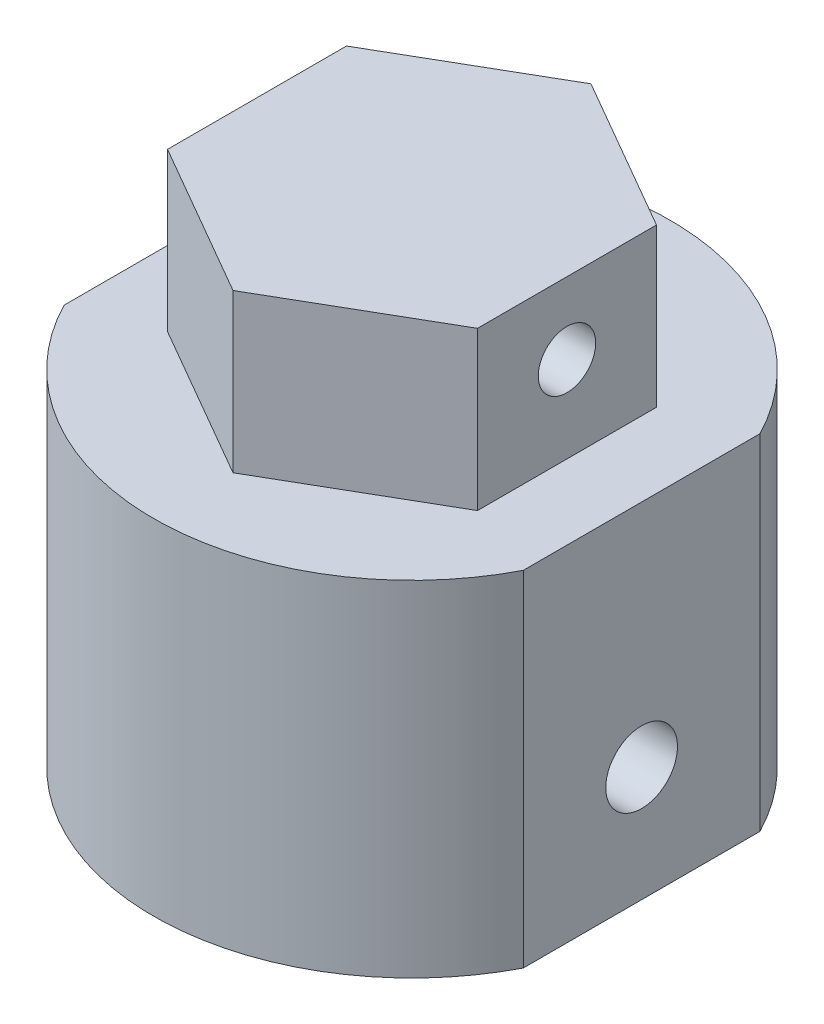
SolidWorks part; units mm, degrees
ref_plane "Plano frontal" through (0, 0, 0) normal (0, 0, 1) x (1, 0, 0)
ref_plane "Plano superior" through (0, 0, 0) normal (0, 1, 0) x (1, 0, 0)
ref_plane "Plano direito" through (0, 0, 0) normal (1, 0, 0) x (0, 0, -1)
sketch "Esboço1" plane through (0, 0, 0) normal (0, 1, 0) x (1, 0, 0)
  circle A0 centre (0, 0) radius 9
  dimension "D1" = 18
extrude "Ressalto-extrusão1" add sketch "Esboço1" along normal blind 12
sketch "Esboço2" plane through (0, 12, 0) normal (0, 1, 0) x (1, 0, 0)
  line L1 (0, 6.2354) -> (-5.4, 3.1177)
  line L2 (-5.4, 3.1177) -> (-5.4, -3.1177)
  line L3 (-5.4, -3.1177) -> (0, -6.2354)
  line L4 (0, -6.2354) -> (5.4, -3.1177)
  line L5 (5.4, -3.1177) -> (5.4, 3.1177)
  line L6 (5.4, 3.1177) -> (0, 6.2354)
  circle A0 centre (0, 0) radius 5.4 construction
  dimension "D1" = 10.8
extrude "Ressalto-extrusão2" add sketch "Esboço2" along normal blind 5.5
sketch "Esboço3" plane through (-5.4, 0, 0) normal (-1, 0, 0) x (0, 0, 1)
  line L1 (9, 12) -> (-9, 12) construction
  circle A0 centre (0, 15) radius 1
  dimension "D1" = 2
  dimension "D2" = 3
extrude "Corte-extrusão1" cut sketch "Esboço3" against normal through all
sketch "Esboço4" plane through (0, 0, 0) normal (0, -1, 0) x (1, 0, 0)
  circle A0 centre (0, 0) radius 3.125
  dimension "D1" = 6.25
extrude "Corte-extrusão2" cut sketch "Esboço4" against normal blind 12
sketch "Esboço5" plane through (0, 0, 0) normal (0, -1, 0) x (1, 0, 0)
  line L0 (-8, -4.1231) -> (-8, 4.1231)
  line L1 (8, -4.1231) -> (8, 4.1231)
  arc A0 (8, -4.1231) -> (8, 4.1231) centre (0, 0) ccw
  arc A1 (-8, 4.1231) -> (-8, -4.1231) centre (0, 0) ccw
  dimension "D3" = 9
  dimension "D4" = 0
  dimension "D1" = 8
  dimension "D2" = 8
extrude "Corte-extrusão3" cut sketch "Esboço5" against normal up to next
sketch "Esboço6" plane through (-8, 0, 0) normal (-1, 0, 0) x (0, 0, 1)
  line L0 (-4.1231, 0) -> (4.1231, 0) construction
  circle A0 centre (0, 4) radius 1.25
  dimension "D1" = 2.5
  dimension "D2" = 4
extrude "Corte-extrusão4" cut sketch "Esboço6" against normal through all
